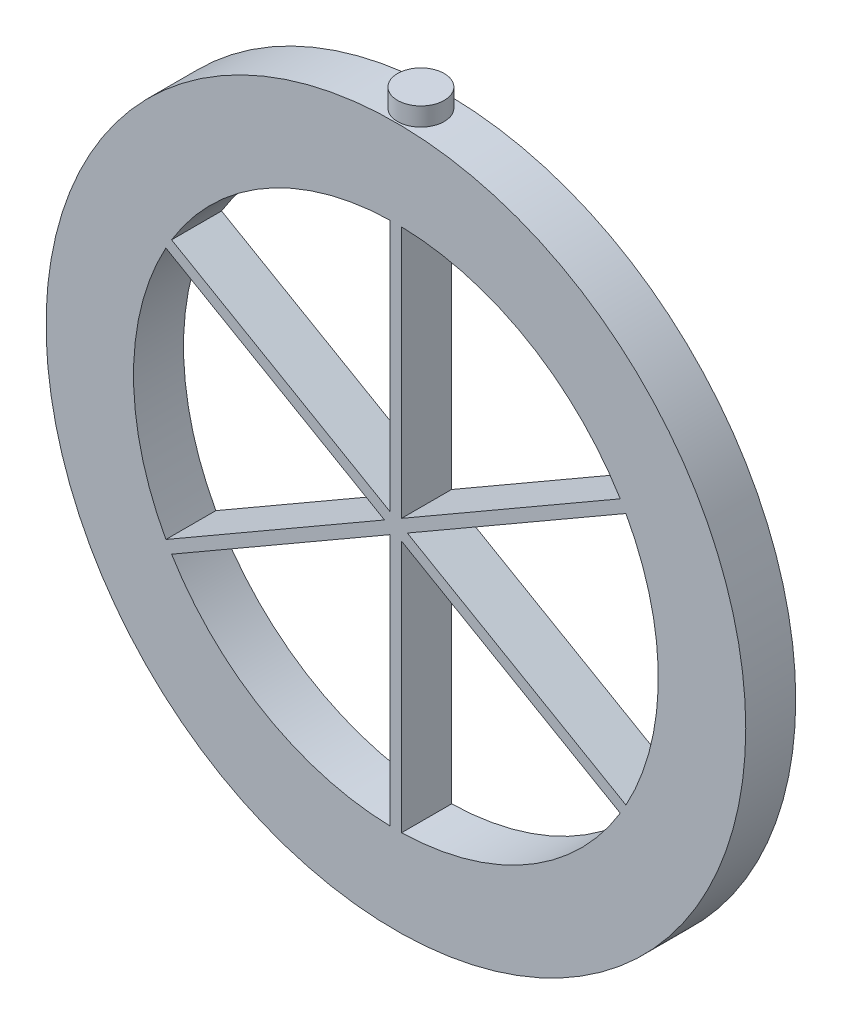
SolidWorks part; units mm, degrees
ref_plane "前视基准面" through (0, 0, 0) normal (0, 0, 1) x (1, 0, 0)
ref_plane "上视基准面" through (0, 0, 0) normal (0, 1, 0) x (1, 0, 0)
ref_plane "右视基准面" through (0, 0, 0) normal (1, 0, 0) x (0, 0, -1)
sketch "草图1" plane through (0, 0, 0) normal (0, 0, 1) x (1, 0, 0)
  line L7 (0, -157.4624) -> (0.0366, -157.4624)
  line L8 (3.4412, -1.9445) -> (3.4412, -1.9868)
  line L9 (-3.4046, -1.9657) -> (-3.4046, -2.0079)
  line L12 (0.0366, -3.9525) -> (0, -3.9736)
  line L14 (-3.4046, 1.9657) -> (-3.4412, 1.9445)
  line L15 (-3.4046, -2.0079) -> (-3.4412, -1.9868)
  line L16 (-3.4046, 1.9657) -> (-3.4412, 1.9868)
  line L17 (0, 3.9313) -> (-0.0366, 3.9525)
  line L18 (-3.4412, 1.9445) -> (-3.4412, 1.9868)
  line L19 (0, 3.9313) -> (0, 3.9736)
  line L20 (3.4046, 1.9657) -> (3.4046, 2.0079)
  line L21 (-0.0366, 3.9525) -> (0, 3.9736)
  line L22 (3.4046, 1.9657) -> (3.4412, 1.9868)
  line L23 (3.4046, -1.9657) -> (3.4412, -1.9445)
  line L24 (3.4046, 2.0079) -> (3.4412, 1.9868)
  line L25 (3.4046, -1.9657) -> (3.4412, -1.9868)
  line L26 (0, -3.9313) -> (0.0366, -3.9525)
  line L27 (-3.4046, -5.9393) -> (-3.4046, -157.5235)
  line L28 (0.0366, -157.4624) -> (0.0366, -157.5235)
  line L29 (-6.8459, -0.0211) -> (-138.0871, 75.751)
  line L30 (0, -3.9313) -> (0, -3.9736)
  line L31 (6.8459, 0.0211) -> (138.1216, 75.8132)
  line L32 (6.8459, 0.0211) -> (138.0871, -75.751)
  line L33 (3.4046, 5.9393) -> (3.4046, 157.5235)
  line L34 (3.4412, -5.9181) -> (3.4412, -157.4624)
  line L35 (-3.4046, -1.9657) -> (-3.4412, -1.9868)
  line L36 (-3.4412, 5.9181) -> (-3.4412, 157.4624)
  line L37 (-6.8459, -0.0211) -> (-138.1216, -75.8132)
  line L38 (-3.4046, -5.9393) -> (-134.6458, -81.7114)
  line L39 (3.4412, -5.9181) -> (134.717, -81.7102)
  line L40 (-3.4412, 5.9181) -> (-134.717, 81.7102)
  line L41 (3.4046, 5.9393) -> (134.6458, 81.7114)
  circle A0 centre (0, 0) radius 210
  arc A1 (-134.6458, -81.7114) -> (-3.4046, -157.4632) centre (0, 0) ccw
  arc A2 (-138.0871, 75.751) -> (-138.0694, -75.7831) centre (0, 0) ccw
  arc A3 (-3.4412, 157.4624) -> (-134.6648, 81.6801) centre (0, 0) ccw
  arc A4 (134.6458, 81.7114) -> (3.4046, 157.4632) centre (0, 0) ccw
  arc A5 (138.0871, -75.751) -> (138.0694, 75.7831) centre (0, 0) ccw
  arc A6 (3.4412, -157.4624) -> (134.6648, -81.6801) centre (0, 0) ccw
  dimension "D3" = 6
extrude "凸台-拉伸1" add sketch "草图1" along normal blind 30
ref_plane "基准面1" through (0, 210, 0) normal (0, 1, 0) x (1, 0, 0)
sketch "草图2" plane through (0, 210, 0) normal (0, 1, 0) x (1, 0, 0)
  line L0 (210, 0) -> (-210, 0) construction
  circle A0 centre (0, -15) radius 14
  dimension "D2" = 28
  dimension "D1" = 15
extrude "凸台-拉伸2" add sketch "草图2" along normal blind 11.0059 separate body
